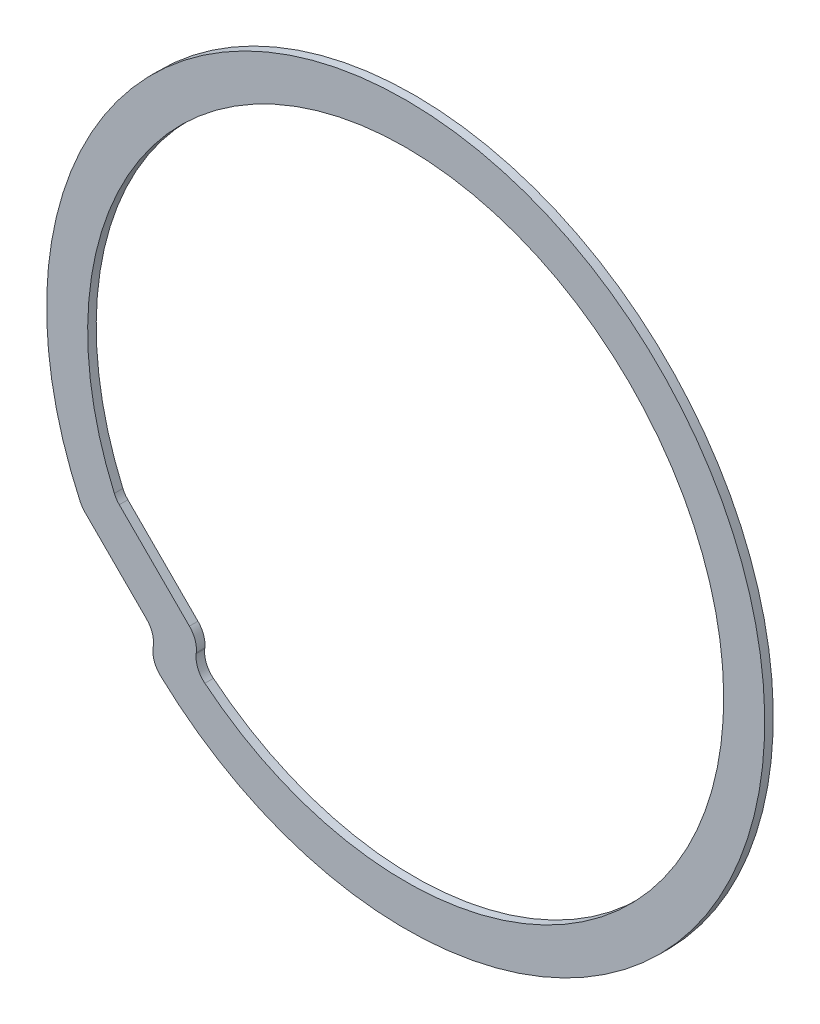
SolidWorks part; units mm, degrees
material "Balsa"
ref_plane "Front Plane" through (0, 0, 0) normal (0, 0, 1) x (1, 0, 0)
ref_plane "Top Plane" through (0, 0, 0) normal (0, 1, 0) x (1, 0, 0)
ref_plane "Right Plane" through (0, 0, 0) normal (1, 0, 0) x (0, 0, -1)
sketch "Sketch1" plane through (0, 0, 0) normal (0, 0, 1) x (1, 0, 0)
  line L0 (0, -110.0909) -> (0, -70.6286) construction
  line L1 (0, 0) -> (0, 245.1538) construction
  line L2 (0, 0) -> (0, 631.6453) construction
  line L3 (-120.188, -34.2725) -> (-93.2472, -61.2132)
  line L4 (0, 0) -> (-284.8905, 0) construction
  line L5 (-93.2472, -61.2132) -> (-94.2927, -70.7977)
  line L8 (-93.2472, -61.2132) -> (-57.7675, -96.693) construction
  arc A0 (-57.7675, -96.693) -> (-120.188, -34.2725) centre (0, 23.495) ccw
  arc A2 (-120.188, -34.2725) -> (-57.7675, -96.693) centre (0, 23.495) ccw construction
  arc A3 (-94.2927, -70.7977) -> (-57.7675, -96.693) centre (0, 23.495) ccw
  point P2 (0, 156.7839)
  point P3 (0, -109.8059)
  point P15 (-93.2472, -61.2132)
  dimension "D1" = 266.5898
  dimension "D2" = 266.7
  dimension "D3" = 23.495
  dimension "D5" = 109.22
  dimension "D6" = 45
  dimension "D7" = 38.1
extrude "Boss-Extrude1" add sketch "Sketch1" along normal mid plane 3.175
sketch "Sketch2" plane through (0, 0, 1.5875) normal (0, 0, 1) x (1, 0, 0)
  line L4 (-77.3048, -55.603) -> (-78.3203, -64.9126)
  line L5 (-107.5191, -25.3887) -> (-77.3048, -55.603)
  line L6 (-77.3048, -55.603) -> (-78.3203, -64.9126)
  line L7 (-107.5191, -25.3887) -> (-77.3048, -55.603)
  arc A2 (-78.3203, -64.9126) -> (-107.5191, -25.3887) centre (0, 23.495) ccw
  arc A3 (-78.3203, -64.9126) -> (-107.5191, -25.3887) centre (0, 23.495) ccw
  dimension "D1" = 15.24
extrude "Cut-Extrude1" cut sketch "Sketch2" against normal up to surface (3.175 mm away) up to face at (-30.5678, -4.3762, -1.5875)
fillet "Fillet1" radius 8.89 6 edges at (-107.5191, -25.3887, 0) (-120.188, -34.2725, 0) (-94.2927, -70.7977, 0) (-93.2472, -61.2132, 0) (-77.3048, -55.603, 0) (-78.3203, -64.9126, 0)
